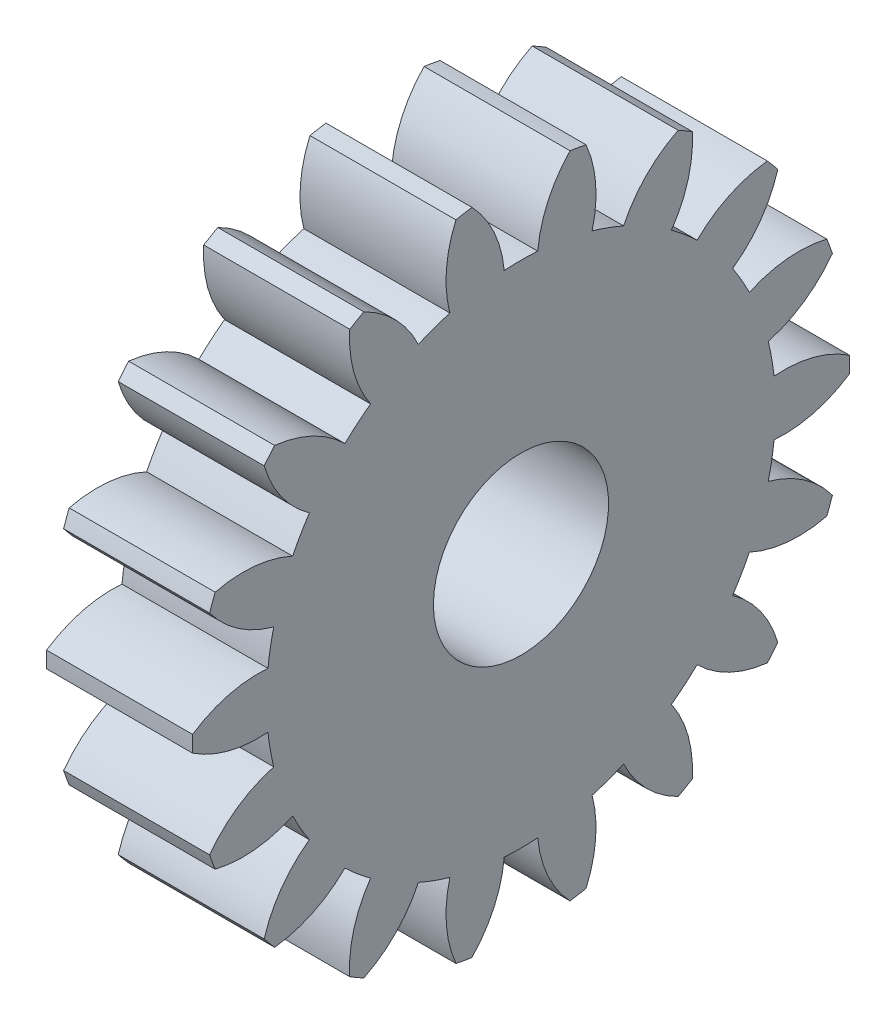
SolidWorks part; units mm, degrees
ref_plane "Plane1" through (0, 0, 0) normal (0, 0, 1) x (1, 0, 0)
ref_plane "Plane2" through (0, 0, 0) normal (0, 1, 0) x (1, 0, 0)
ref_plane "Plane3" through (0, 0, 0) normal (1, 0, 0) x (0, 0, -1)
sketch "HoldingSke" plane through (0, 0, 0) normal (0, 1, 0) x (1, 0, 0)
  line L0 (0, 0) -> (0.8454, -0.2747)
  line L1 (-15, 0) -> (100, 0) construction
  line L2 (0, 0) -> (-2.1039, 2.3779)
  line L3 (0, 0) -> (-11.863, 4.5341)
  line L4 (0, 0) -> (8.2133, 2.6687)
  line L5 (0, 0) -> (-46.8476, -17.4728)
  line L6 (0, 0) -> (-4.1448, -2.7965)
  line L7 (-2.1039, 2.3779) -> (8.6586, 51.2059)
  line L8 (-76.2, 54.61) -> (-75.2, 54.61)
  line L9 (-71.009, 38.7566) -> (-53.1078, 45.2721)
  line L10 (-76.2, 71.12) -> (104.1128, 71.12)
  line L11 (0, 0) -> (-5, 0)
  line L12 (-76.2, 101.6) -> (-76.158, 101.6)
  line L13 (24.9733, 27.94) -> (52.9518, 28.4284)
  line L14 (24.9733, 27.94) -> (24.9743, 27.94)
  line L15 (24.9733, 27.94) -> (100.4006, 29.5858)
  line L16 (-63.627, -1.125) -> (-12.827, -1.125)
  circle A0 centre (0, 0) radius 3
  circle A1 centre (0, 0) radius 8.7177
  circle A2 centre (0, 0) radius 37.5
  circle A3 centre (0, 0) radius 3
  dimension "MHD" = 17.4355
  dimension "Hub_dia" = 75
  dimension "Bore" = 6
  dimension "MBD" = 6
  dimension "Num_teeth" = 18
  dimension "Pitch" = 0.8889
  dimension "Overall_len" = 50
  dimension "Show_teeth" = 18
  dimension "Thickness" = 5
  dimension "OAL" = 50.0001
  dimension "T_dim" = 1
  dimension "Ap" = 20
  dimension "H" = 19.05
  dimension "Pitch_radius" = 180.3128
  dimension "Width" = 5
  dimension "Backlash" = 0.042
  dimension "Addendum_fac" = 1
  dimension "Dedendum_fac" = 1.25
  dimension "Clearance_fac" = 0.25
  dimension "Dedendum_add" = 0.001
  dimension "Module" = 1.125
sketch "BasProSke" plane through (0, 0, 0) normal (0, 1, 0) x (1, 0, 0)
  line L0 (-10, 0) -> (60, 0) construction
  line L1 (0, 0) -> (0, 11.25)
  line L2 (0, 0) -> (5, 0)
  line L3 (5, 0) -> (5, 11.25)
  line L4 (5, 11.25) -> (0, 11.25)
  dimension "Thickness" = 5
  dimension "Diameter" = 22.5
revolve "Base-Revolve" add sketch "BasProSke" angle 360 about L0
sketch "TooCutSke" plane through (0, 0, 0) normal (1, 0, 0) x (0, 0, -1)
  line L1 (0, 0) -> (0, 107) construction
  line L2 (0, 0) -> (-0.9559, 10.0798) construction
  line L3 (0, 0) -> (-3.5051, 19.8786) construction
  line L4 (-0.9559, 10.0798) -> (-1.7526, 9.9393) construction
  arc A0 (0.5734, 8.6989) -> (-0.5734, 8.6989) centre (0, 0) ccw
  arc A1 (1.7004, 11.1464) -> (-1.7004, 11.1464) centre (0, 0) ccw
  circle A2 centre (0, 0) radius 10.125 construction
  circle A3 centre (0, 0) radius 9.5144 construction
  arc A4 (-0.5734, 8.6989) -> (-1.7004, 11.1464) centre (-4.6061, 8.3251) ccw
  arc A5 (1.7004, 11.1464) -> (0.5734, 8.6989) centre (4.6061, 8.3251) ccw
  dimension "Root_dia" = 17.4355
  dimension "Overcut_dia" = 22.5508
  dimension "Pitch_dia" = 20.25
  dimension "Base_dia" = 19.0288
  dimension "Flank_rad" = 4.05
  dimension "Half_ang" = 10
  dimension "Half_CT" = 0.809
extrude "ToothCut" cut sketch "TooCutSke" along normal through all
fillet "Breaks" [suppressed] radius 0.0225
fillet "RootFillets" [suppressed] radius 0.2823
pattern_circular "TeethCuts" count 18 every 20 about axis through (-10, 0, 0) along (1, 0, 0) of "ToothCut", "RootFillets", "Breaks"
sketch "HubNeaOneSke" plane through (0, 0, 0) normal (-1, 0, 0) x (0, 0, 1)
  circle A0 centre (0, 0) radius 8.7177
  dimension "Diameter" = 17.4355
extrude "HubNearOne" [suppressed] add sketch "HubNeaOneSke" along normal blind 45.0001
sketch "HubNeaBotSke" plane through (0, 0, 0) normal (-1, 0, 0) x (0, 0, 1)
  circle A0 centre (0, 0) radius 8.7177
  dimension "Diameter" = 17.4355
extrude "HubNearBoth" [suppressed] add sketch "HubNeaBotSke" along normal blind 22.5
ref_plane "FarPln" through (5, 0, 0) normal (1, 0, 0) x (0, 0, -1)
sketch "HubFarSke" plane through (5, 0, 0) normal (1, 0, 0) x (0, 0, -1)
  circle A0 centre (0, 0) radius 8.7177
  dimension "Diameter" = 17.4355
extrude "HubFar" [suppressed] add sketch "HubFarSke" along normal blind 22.5
sketch "BorSke" plane through (0, 0, 0) normal (1, 0, 0) x (0, 0, -1)
  circle A0 centre (0, 0) radius 3
  dimension "Diameter" = 6
extrude "Bore" cut sketch "BorSke" along normal mid plane 100.0001
sketch "KeySke" plane through (0, 0, 0) normal (1, 0, 0) x (0, 0, -1)
  line L0 (-1, 0) -> (-1, 4)
  line L1 (-1, 4) -> (1, 4)
  line L2 (1, 4) -> (1, 0)
  line L3 (0, 0) -> (0, 34) construction
  line L4 (-1, 0) -> (1, 0)
  dimension "Offset" = 4
  dimension "Width" = 2
extrude "Keyway" [suppressed] cut sketch "KeySke" along normal mid plane 100.0001
pattern_circular "Keyway2" [suppressed] count 2 every 90 about axis through (-10, 0, 0) along (1, 0, 0)
equation "' \"Module@HoldingSke\" = 6.35"
equation "' \"Num_teeth@HoldingSke\" = 12"
equation "' \"Ap@HoldingSke\" =  20"
equation "' \"Ap@HoldingSke\" = 20"
equation "' \"Width@HoldingSke\" = 0.5 * 25.4"
equation "' \"Hub_dia@HoldingSke\"= 1 * 25.4"
equation "' \"Hub_dia@HoldingSke\" = 1 * 25.4"
equation "' \"Overall_len@HoldingSke\" = 1.0 * 25.4"
equation "' \"Bore@HoldingSke\" = 0.75 * 25.4"
equation "' \"T_dim@HoldingSke\" = 0.1 * 25.4"
equation "' \"Width@KeySke\" = 0.25 * 25.4"
equation "' \"Show_teeth@HoldingSke\" = 13"
equation "' \"Backlash@HoldingSke\" = 0.009 * 25.4"
equation "' \"Addendum_fac@HoldingSke\" = 1.0"
equation "' \"Dedendum_fac@HoldingSke\" = 1.25"
equation "' \"Dedendum_add@HoldingSke\" = 0.00005 * 25.4"
equation "' \"Clearance_fac@HoldingSke\" = 0.25"
equation "\"Pitch@HoldingSke\" = 1 / \"Module@HoldingSke\""
equation "\"Overcut_dia@TooCutSke\" = (\"Num_teeth@HoldingSke\" + 2 * \"Addendum_fac@HoldingSke\") / \"Pitch@HoldingSke\" + 0.002 * 25.4"
equation "\"Pitch_dia@TooCutSke\" = \"Num_teeth@HoldingSke\" / \"Pitch@HoldingSke\""
equation "\"Base_dia@TooCutSke\" = \"Num_teeth@HoldingSke\" / \"Pitch@HoldingSke\" * cos((\"Ap@HoldingSke\"  * 3.14159265 / 180))"
equation "\"Root_dia@TooCutSke\" = (\"Num_teeth@HoldingSke\" + 2) / \"Pitch@HoldingSke\" - 2 * (\"Addendum_fac@HoldingSke\" + \"Dedendum_fac@HoldingSke\") / \"Pitch@HoldingSke\" - \"Dedendum_add@HoldingSke\" * 2"
equation "\"Half_ang@TooCutSke\" = 180 / \"Num_teeth@HoldingSke\""
equation "\"Half_CT@TooCutSke\" = \"Num_teeth@HoldingSke\" / \"Pitch@HoldingSke\" * sin((3.14159265 / 2 / \"Num_teeth@HoldingSke\")) / 2 - 7 * \"Backlash@HoldingSke\" / 4"
equation "\"Flank_rad@TooCutSke\" = \"Num_teeth@HoldingSke\" / \"Pitch@HoldingSke\" / 5"
equation "\"Radius@RootFillets\" = \"Clearance_fac@HoldingSke\" / \"Pitch@HoldingSke\" + \"Dedendum_add@HoldingSke\""
equation "\"Break_rad@Breaks\" = 0.02 / \"Pitch@HoldingSke\""
equation "\"Thickness@HoldingSke\" = \"Width@HoldingSke\""
equation "\"OAL@HoldingSke\" = \"Thickness@HoldingSke\""
equation "\"MHD@HoldingSke\" = (\"Num_teeth@HoldingSke\" + 2) / \"Pitch@HoldingSke\" - 2 * (\"Addendum_fac@HoldingSke\" + \"Dedendum_fac@HoldingSke\")  / \"Pitch@HoldingSke\" - \"Dedendum_add@HoldingSke\" * 2"
equation "\"MBD@HoldingSke\" = (\"Num_teeth@HoldingSke\" + 2) / \"Pitch@HoldingSke\" - 2 * (\"Addendum_fac@HoldingSke\" + \"Dedendum_fac@HoldingSke\")  / \"Pitch@HoldingSke\" - \"Dedendum_add@HoldingSke\" * 2 - 0.002 * 25.4"
equation "\"MHD@HoldingSke\" = ((sgn( \"MHD@HoldingSke\" - \"Hub_dia@HoldingSke\" )-1)*( \"MHD@HoldingSke\" - \"Hub_dia@HoldingSke\" ))/-2+ \"Hub_dia@HoldingSke\""
equation "\"MBD@HoldingSke\" = ((sgn( \"MBD@HoldingSke\" - \"Bore@HoldingSke\" )-1)*( \"MBD@HoldingSke\" - \"Bore@HoldingSke\" ))/-2+ \"Bore@HoldingSke\""
equation "\"OAL@HoldingSke\" = ((sgn( \"OAL@HoldingSke\" - \"Overall_len@HoldingSke\" )+1)*( \"OAL@HoldingSke\" - \"Overall_len@HoldingSke\" ))/2 + \"Overall_len@HoldingSke\" + 0.000002 * 25.4"
equation "\"Num_teeth@TeethCuts\" = int( \"Show_teeth@HoldingSke\" ) + 1"
equation "\"Num_teeth@TeethCuts\" = ((sgn( \"Num_teeth@TeethCuts\" - \"Num_teeth@HoldingSke\" )-1)*( \"Num_teeth@TeethCuts\" - \"Num_teeth@HoldingSke\" ))/-2+ \"Num_teeth@HoldingSke\""
equation "\"Num_teeth@TeethCuts\" = ((sgn( \"Num_teeth@TeethCuts\" - 2.0)+1)*( \"Num_teeth@TeethCuts\" - 2.0))/2 +2.0"
equation "\"Angle@TeethCuts\" = 360.0 / \"Num_teeth@HoldingSke\""
equation "\"Diameter@BasProSke\" = (\"Num_teeth@HoldingSke\" + 2 * \"Addendum_fac@HoldingSke\") / \"Pitch@HoldingSke\""
equation "\"Thickness@BasProSke\"  = \"Thickness@HoldingSke\""
equation "' \"Fillet_rad@BasProSke\" =  \"Thickness@HoldingSke\" * 0.05"
equation "' \"Fillet_rad@BasProSke\" = \"Thickness@HoldingSke\" * 0.05"
equation "\"MHD@HoldingSke\" = ((sgn( \"MHD@HoldingSke\" - \"Root_dia@TooCutSke\" )-1)*( \"MHD@HoldingSke\" - \"Root_dia@TooCutSke\" ))/-2+ \"Root_dia@TooCutSke\""
equation "\"Diameter@HubNeaOneSke\" = \"MHD@HoldingSke\""
equation "\"Length@HubNearOne\" = \"OAL@HoldingSke\" - \"Thickness@BasProSke\""
equation "\"Diameter@HubNeaBotSke\" = \"MHD@HoldingSke\""
equation "\"Length@HubNearBoth\" = ( \"OAL@HoldingSke\" - \"Thickness@BasProSke\" ) / 2.0"
equation "\"Thickness@FarPln\" = \"Thickness@BasProSke\""
equation "\"Diameter@HubFarSke\" = \"MHD@HoldingSke\""
equation "\"Length@HubFar\" = ( \"OAL@HoldingSke\" - \"Thickness@BasProSke\" ) / 2.0"
equation "\"Diameter@BorSke\" = \"MBD@HoldingSke\""
equation "\"D1@Bore\" = \"OAL@HoldingSke\" * 2.0"
equation "\"D1@Keyway\" = \"OAL@HoldingSke\" * 2.0"
equation "\"Offset@KeySke\" = \"T_dim@HoldingSke\" + \"MBD@HoldingSke\" / 2.0"
